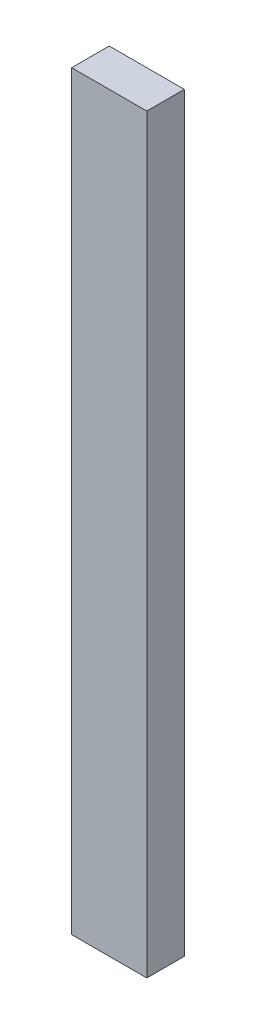
SolidWorks part; units mm, degrees
ref_plane "Front Plane" through (0, 0, 0) normal (0, 0, 1) x (1, 0, 0)
ref_plane "Top Plane" through (0, 0, 0) normal (0, 1, 0) x (1, 0, 0)
ref_plane "Right Plane" through (0, 0, 0) normal (1, 0, 0) x (0, 0, -1)
sketch "Sketch1" plane through (0, 0, 0) normal (0, 1, 0) x (1, 0, 0)
  line L1 (0, 0) -> (-100, 0)
  line L2 (0, 0) -> (0, 50)
  line L3 (0, 50) -> (-100, 50)
  line L4 (-100, 0) -> (-100, 50)
  dimension "D1" = 100
  dimension "D2" = 50
extrude "Boss-Extrude1" add sketch "Sketch1" along normal blind 1000
